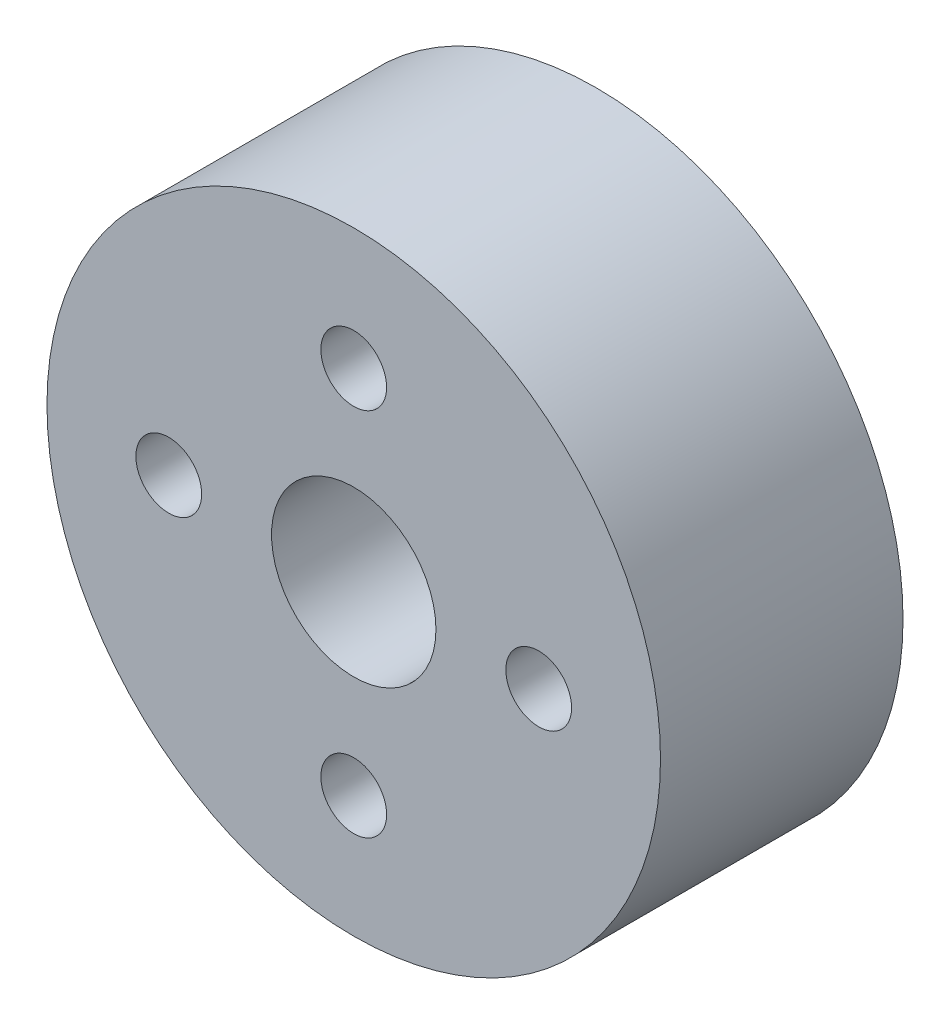
SolidWorks part; units mm, degrees
ref_plane "Спереди" through (0, 0, 0) normal (0, 0, 1) x (1, 0, 0)
ref_plane "Сверху" through (0, 0, 0) normal (0, 1, 0) x (1, 0, 0)
ref_plane "Справа" through (0, 0, 0) normal (1, 0, 0) x (0, 0, -1)
other "Configuration Table"
sketch "Эскиз1" plane through (0, 0, 0) normal (0, 0, 1) x (1, 0, 0)
  circle A0 centre (0, 0) radius 14.925
  circle A1 centre (0, 0) radius 4
  circle A2 centre (-9, 0) radius 1.6
  circle A3 centre (9, 0) radius 1.6
  circle A4 centre (0, 9) radius 1.6
  circle A5 centre (0, -9) radius 1.6
extrude "05_Pan_horn_journal" add sketch "Эскиз1" along normal blind 11.8
